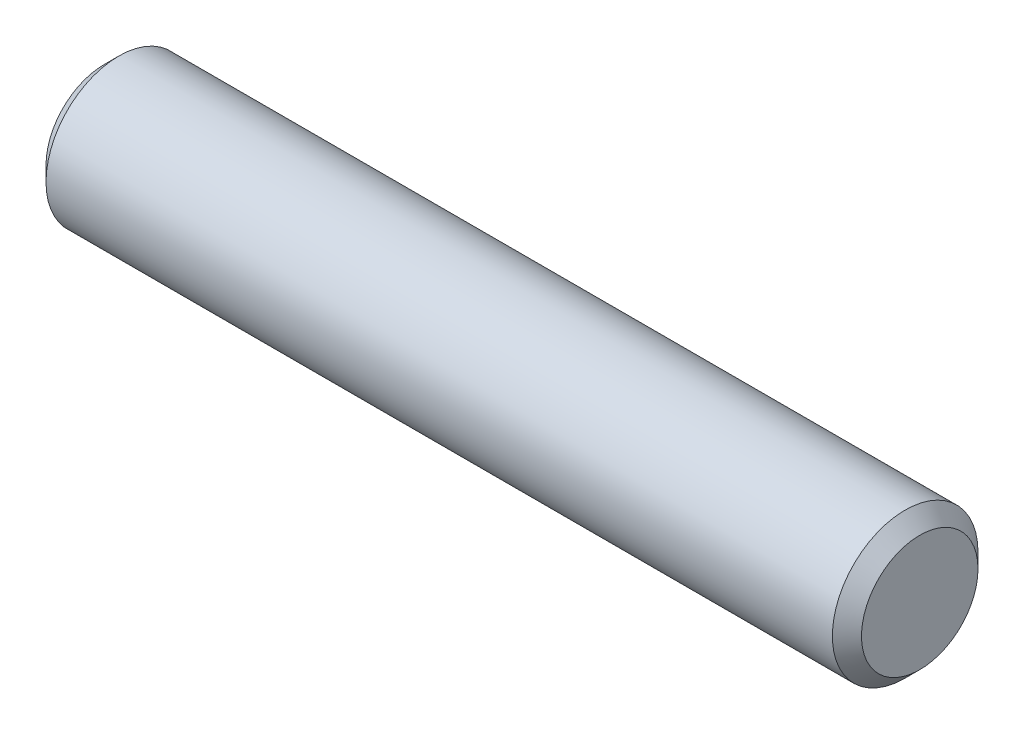
SolidWorks part; units mm, degrees
ref_plane "Front Plane" through (0, 0, 0) normal (0, 0, 1) x (1, 0, 0)
ref_plane "Top Plane" through (0, 0, 0) normal (0, 1, 0) x (1, 0, 0)
ref_plane "Right Plane" through (0, 0, 0) normal (1, 0, 0) x (0, 0, -1)
sketch "Sketch1" plane through (0, 0, 0) normal (0, 1, 0) x (1, 0, 0)
  line L1 (0, 0) -> (-28, 0)
  line L2 (0, 0) -> (0, 2.5)
  line L3 (0, 2.5) -> (-28, 2.5)
  line L4 (-28, 0) -> (-28, 2.5)
  dimension "D1" = 28
  dimension "D2" = 2.5
revolve "Revolve1" add sketch "Sketch1" angle 360 about L1
chamfer "Chamfer1" distance 0.5 angle 45 2 edges at (0, 0, -2.5) (-28, 0, -2.5)
